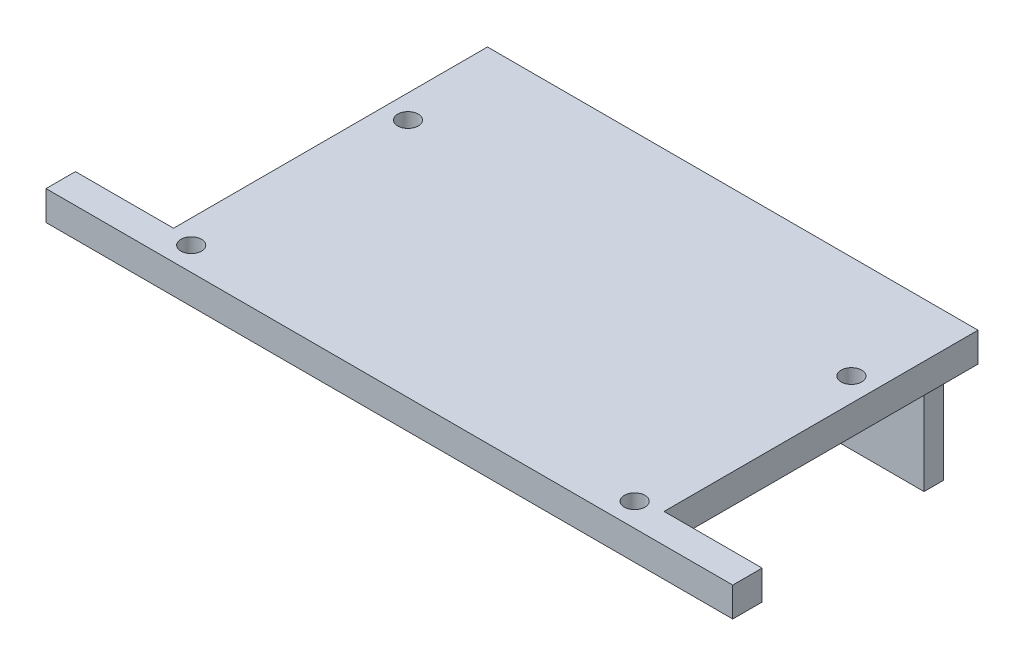
SolidWorks part; units mm, degrees
ref_plane "Front Plane" through (0, 0, 0) normal (0, 0, 1) x (1, 0, 0)
ref_plane "Top Plane" through (0, 0, 0) normal (0, 1, 0) x (1, 0, 0)
ref_plane "Right Plane" through (0, 0, 0) normal (1, 0, 0) x (0, 0, -1)
sketch "Sketch1" plane through (0, 0, 0) normal (0, 1, 0) x (1, 0, 0)
  line L1 (-26.2389, 17.5585) -> (23.7611, 17.5585)
  line L2 (-26.2389, 17.5585) -> (-26.2389, -14.4415)
  line L3 (-26.2389, -17.4415) -> (23.7611, -17.4415)
  line L4 (23.7611, 17.5585) -> (23.7611, -14.4415)
  line L5 (-26.2389, -17.4415) -> (-36.2389, -17.4415)
  line L7 (-26.2389, -14.4415) -> (-36.2389, -14.4415)
  line L8 (-36.2389, -17.4415) -> (-36.2389, -14.4415)
  line L9 (23.7611, -17.4415) -> (33.7611, -17.4415)
  line L11 (23.7611, -14.4415) -> (33.7611, -14.4415)
  line L12 (33.7611, -17.4415) -> (33.7611, -14.4415)
  dimension "D1" = 35
  dimension "D2" = 50
  dimension "D3" = 3
  dimension "D4" = 3
  dimension "D5" = 10
  dimension "D6" = 10
extrude "Boss-Extrude1" add sketch "Sketch1" along normal blind 3
sketch "Sketch2" plane through (0, 3, 0) normal (0, 1, 0) x (1, 0, 0)
  line L0 (-26.2389, 17.5585) -> (-26.2389, -14.4415) construction
  line L1 (-36.2389, -17.4415) -> (33.7611, -17.4415) construction
  line L2 (23.7611, -14.4415) -> (23.7611, 17.5585) construction
  circle A0 centre (-23.8389, -15.0415) radius 1.05
  circle A1 centre (21.3611, -15.0415) radius 1.05
  dimension "D1" = 2.1
  dimension "D2" = 2.1
  dimension "D3" = 2.4
  dimension "D4" = 2.4
  dimension "D5" = 2.4
  dimension "D6" = 2.4
extrude "Cut-Extrude1" cut sketch "Sketch2" against normal blind 3
sketch "Sketch3" plane through (0, 3, 0) normal (0, 1, 0) x (1, 0, 0)
  line L0 (-26.2389, 17.5585) -> (-26.2389, -14.4415) construction
  line L1 (23.7611, 17.5585) -> (-26.2389, 17.5585) construction
  line L2 (23.7611, -14.4415) -> (23.7611, 17.5585) construction
  circle A0 centre (-23.8389, 7.0585) radius 1.05
  circle A1 centre (21.3611, 7.0585) radius 1.05
  dimension "D1" = 2.1
  dimension "D2" = 2.1
  dimension "D3" = 2.4
  dimension "D4" = 10.5
  dimension "D5" = 2.4
  dimension "D6" = 10.5
extrude "Cut-Extrude2" cut sketch "Sketch3" against normal blind 3
sketch "Sketch4" plane through (0, 0, 0) normal (0, -1, 0) x (1, 0, 0)
  line L0 (23.7611, -17.5585) -> (-26.2389, -17.5585) construction
  line L1 (20.2611, -17.5585) -> (5.2611, -17.5585)
  line L2 (20.2611, -17.5585) -> (20.2611, -15.5585)
  line L3 (20.2611, -15.5585) -> (5.2611, -15.5585)
  line L4 (5.2611, -17.5585) -> (5.2611, -15.5585)
  line L5 (23.7611, 14.4415) -> (23.7611, -17.5585) construction
  line L6 (-22.7389, -17.5585) -> (-18.7389, -17.5585)
  line L7 (-22.7389, -17.5585) -> (-22.7389, -15.5585)
  line L8 (-22.7389, -15.5585) -> (-18.7389, -15.5585)
  line L9 (-18.7389, -17.5585) -> (-18.7389, -15.5585)
  line L10 (-26.2389, -17.5585) -> (-26.2389, 14.4415) construction
  dimension "D1" = 3.5
  dimension "D2" = 3.5
  dimension "D3" = 4
  dimension "D4" = 2
  dimension "D5" = 15
  dimension "D6" = 2
extrude "Boss-Extrude2" add sketch "Sketch4" along normal blind 12
